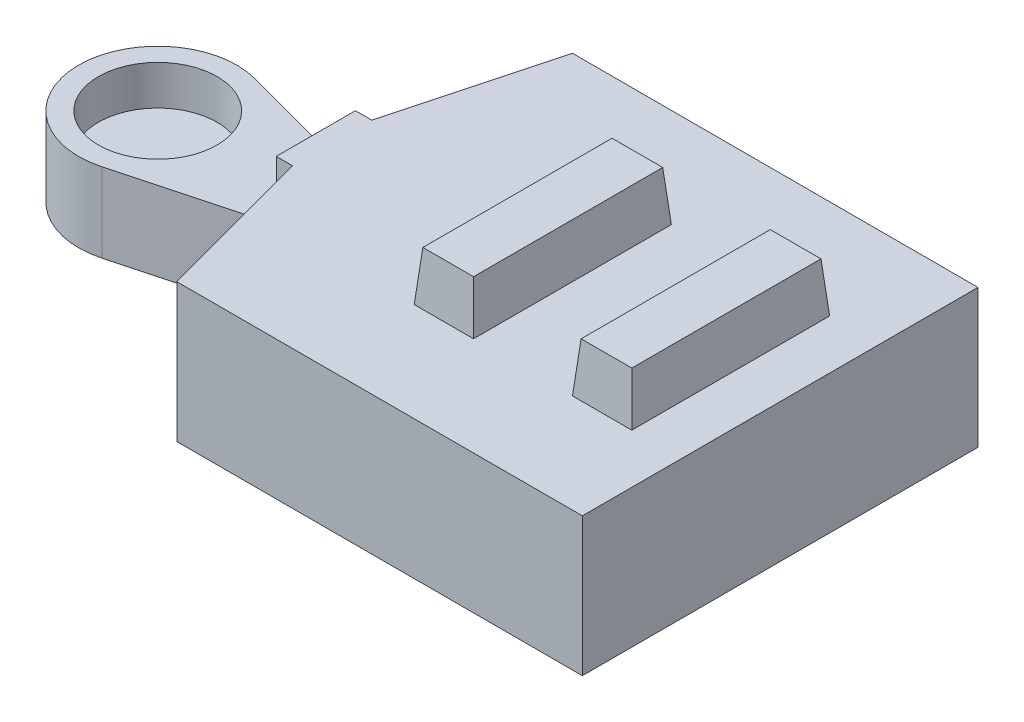
SolidWorks part; units mm, degrees
ref_plane "Front Plane" through (0, 0, 0) normal (0, 0, 1) x (1, 0, 0)
ref_plane "Top Plane" through (0, 0, 0) normal (0, 1, 0) x (1, 0, 0)
ref_plane "Right Plane" through (0, 0, 0) normal (1, 0, 0) x (0, 0, -1)
sketch "Sketch1" plane through (0, 0, 0) normal (0, 1, 0) x (1, 0, 0)
  line L1 (10.9617, 10) -> (31.4641, 10)
  line L3 (10.9617, -10) -> (31.4641, -10)
  line L4 (31.4641, 10) -> (31.4641, -10)
  line L8 (0, 0) -> (-0.9659, -0.2588) construction
  line L9 (7.9907, 2) -> (8.8181, 2)
  line L11 (7.9907, -2) -> (8.8181, -2)
  line L13 (7.9262, -2.5349) -> (8.7026, -5.4327) construction
  line L14 (-0.9659, -0.2588) -> (0.1988, -4.6055) construction
  line L15 (0.1988, -4.6055) -> (7.9262, -2.5349) construction
  line L16 (0.0694, -4.1225) -> (9.7286, -1.5343) construction
  line L17 (8.2237, 0.2182) -> (9.9267, -6.1374) construction
  line L18 (1.0353, -3.8637) -> (7.9907, -2)
  line L19 (7.5, -7.75) -> (8, -7.75) construction
  line L20 (8.7026, -5.4327) -> (10.5313, -4.9427) construction
  line L21 (8.8181, -2) -> (9.6685, -5.1739)
  line L23 (-5.225, 0) -> (5.225, 0) construction
  line L24 (8.8181, 2) -> (9.6685, 5.1739)
  line L25 (1.0353, 3.8637) -> (7.9907, 2)
  line L26 (9.4641, 8.9441) -> (9.4641, -8.2746) construction
  line L27 (8.7026, -5.4327) -> (9.7379, -9.2964) construction
  line L28 (-0.5, 9.3147) -> (-0.5, -9.5) construction
  line L29 (-0.5, 6.75) -> (-0.5, 10) construction
  line L30 (-2.5, -9.5) -> (0.5, -9.5) construction
  line L31 (-0.5, -9.5) -> (-0.5, -7.25) construction
  line L32 (9.9267, -6.1374) -> (10.9617, -10) construction
  line L33 (9.6685, -5.1739) -> (10.9617, -10)
  line L34 (9.6685, 5.1739) -> (10.9617, 10)
  arc A1 (0, 4) -> (0, -4) centre (0, 0) ccw
  arc A2 (1.0353, 3.8637) -> (1.0353, -3.8637) centre (0, 0) ccw
  point P14 (4, 0)
  dimension "D3" = 4
  dimension "D2" = 4
  dimension "D4" = 20
  dimension "D6" = 1
  dimension "D7" = 4.5
  dimension "D8" = 8
  dimension "D9" = 0.5
  dimension "D10" = 10
  dimension "D11" = 1
extrude "Boss-Extrude1" add sketch "Sketch1" along normal blind 4
sketch "Sketch2" plane through (0, 4, 0) normal (0, 1, 0) x (1, 0, 0)
  circle A0 centre (0, 0) radius 3
extrude "Cut-Extrude1" cut sketch "Sketch2" against normal blind 2
sketch "Sketch4" plane through (0, 0, 0) normal (0, 0, 1) x (1, 0, 0)
sketch "Sketch18" plane through (0, 4, 0) normal (0, 1, 0) x (1, 0, 0)
  line L0 (7.9907, -2) -> (8.8181, -2)
  line L1 (8.8181, -2) -> (10.9617, -10)
  line L2 (7.9907, -2) -> (7.9907, 2)
  line L3 (7.9907, 2) -> (8.8181, 2)
  line L4 (8.8181, 2) -> (10.9617, 10)
  line L6 (10.9617, 10) -> (31.4641, 10) construction
  line L7 (10.9617, 10) -> (10.9617, -10)
  line L8 (10.9617, -10) -> (31.4641, -10) construction
  line L10 (7.9907, 0) -> (0, 0) construction
  line L11 (10.9617, 10) -> (31.4641, 10) construction
extrude "Boss-Extrude2" add sketch "Sketch18" along normal up to vertex (3 mm away)
sketch "Sketch24" plane through (0, 4, 0) normal (0, 1, 0) x (1, 0, 0)
  line L0 (10.9617, -10) -> (10.9617, 10)
  line L3 (10.9617, -10) -> (31.4641, -10)
  line L4 (31.4641, 10) -> (31.4641, -10)
  line L5 (10.9617, 10) -> (31.4641, 10)
extrude "Boss-Extrude4" add sketch "Sketch24" along normal up to surface (3 mm away) up to face at (9.2568, 7, 0)
sketch "Sketch21" plane through (0, 7, 0) normal (0, 1, 0) x (1, 0, 0)
  line L1 (10.9617, 10) -> (10.9617, -10)
  line L5 (7.9907, 2) -> (7.9907, -2)
  line L8 (-0.5, 4.4811) -> (-0.5, -4.5) construction
  line L9 (7.9907, 2) -> (8.8181, 2)
  line L10 (8.8181, 2) -> (10.9617, 10)
  line L11 (7.9907, -2) -> (8.8181, -2)
  line L12 (8.8181, -2) -> (10.9617, -10)
revolve "Revolve1" [suppressed] add sketch "Sketch21" about L8
sketch "Sketch25" [suppressed] plane through (0, 0, -10) normal (0, 0, -1) x (-1, 0, 0)
  line L0 (-10.9617, 7) -> (-10.9617, 0)
  line L1 (-10.9617, 0) -> (-8.5758, 0)
  arc A0 (-10.9617, 7) -> (-8.5758, 0) centre (0.5, 7) ccw
  arc A2 (-10.9617, 7) -> (-8.5758, 0) centre (0.5, 7) ccw construction
extrude "Boss-Extrude5" [suppressed] add sketch "Sketch25" against normal through all
sketch "Sketch26" plane through (0, 7, 0) normal (0, 1, 0) x (1, 0, 0)
  line L0 (31.4641, -10) -> (31.4641, 10) construction
  line L1 (31.4641, 0) -> (19.4641, 0) construction
  line L2 (31.4641, 0) -> (27.4641, 0) construction
  line L4 (25.9641, 5) -> (28.9641, 5)
  line L5 (25.9641, 5) -> (25.9641, -5)
  line L6 (25.9641, -5) -> (28.9641, -5)
  line L7 (28.9641, 5) -> (28.9641, -5)
  line L8 (25.9641, 5) -> (28.9641, -5) construction
  line L9 (25.9641, -5) -> (28.9641, 5) construction
  line L10 (17.9641, 5) -> (20.9641, 5)
  line L11 (17.9641, 5) -> (17.9641, -5)
  line L12 (17.9641, -5) -> (20.9641, -5)
  line L13 (20.9641, 5) -> (20.9641, -5)
  line L14 (17.9641, 5) -> (20.9641, -5) construction
  line L15 (17.9641, -5) -> (20.9641, 5) construction
  dimension "D1" = 10
  dimension "D2" = 3
  dimension "D3" = 3
  dimension "D4" = 10
extrude "Boss-Extrude6" add sketch "Sketch26" along normal blind 2.5
sketch "Sketch27" plane through (0, 0, -5) normal (0, 0, -1) x (-1, 0, 0)
  line L0 (-28.9641, 7) -> (-28.7454, 9.5)
  line L1 (-28.9641, 9.5) -> (-25.9641, 9.5) construction
  line L2 (-28.9641, 9.5) -> (-28.9641, 7) construction
  line L3 (-25.9641, 7) -> (-26.1828, 9.5)
  line L4 (-25.9641, 9.5) -> (-25.9641, 7) construction
  line L5 (-28.9641, 7) -> (-28.9641, 9.5)
  line L6 (-28.9641, 9.5) -> (-28.7454, 9.5)
  line L7 (-26.1828, 9.5) -> (-25.9641, 9.5)
  line L8 (-25.9641, 9.5) -> (-25.9641, 7)
  line L9 (-20.9641, 7) -> (-20.7454, 9.5)
  line L10 (-20.9641, 9.5) -> (-17.9641, 9.5) construction
  line L11 (-17.9641, 7) -> (-18.1828, 9.5)
  line L12 (-20.9641, 9.5) -> (-20.9641, 7) construction
  line L13 (-17.9641, 9.5) -> (-17.9641, 7) construction
  line L14 (-20.9641, 7) -> (-20.9641, 9.5)
  line L15 (-20.9641, 9.5) -> (-20.7454, 9.5)
  line L16 (-17.9641, 7) -> (-17.9641, 9.5)
  line L17 (-17.9641, 9.5) -> (-18.1828, 9.5)
  dimension "D1" = 5
  dimension "D2" = 5
  dimension "D3" = 5
  dimension "D4" = 5
extrude "Cut-Extrude2" cut sketch "Sketch27" against normal up to surface (10 mm away) up to face at (27.4641, 8.25, 5)
sketch "Sketch28" plane through (0, 0, 0) normal (1, 0, 0) x (0, 0, -1)
  line L0 (-5, 7) -> (-4.7813, 9.5)
  line L1 (-5, 9.5) -> (5, 9.5) construction
  line L2 (5, 7) -> (4.7813, 9.5)
  line L3 (-5, 9.5) -> (-5, 7) construction
  line L4 (5, 7) -> (5, 9.5) construction
  line L5 (-5, 7) -> (-5, 9.5)
  line L6 (-5, 9.5) -> (-4.7813, 9.5)
  line L7 (4.7813, 9.5) -> (5, 9.5)
  line L8 (5, 9.5) -> (5, 7)
  dimension "D1" = 5
  dimension "D2" = 5
extrude "Cut-Extrude3" cut sketch "Sketch28" against normal through all both and the other way through all contours L6 L0 L5 | L8 L2 L7
